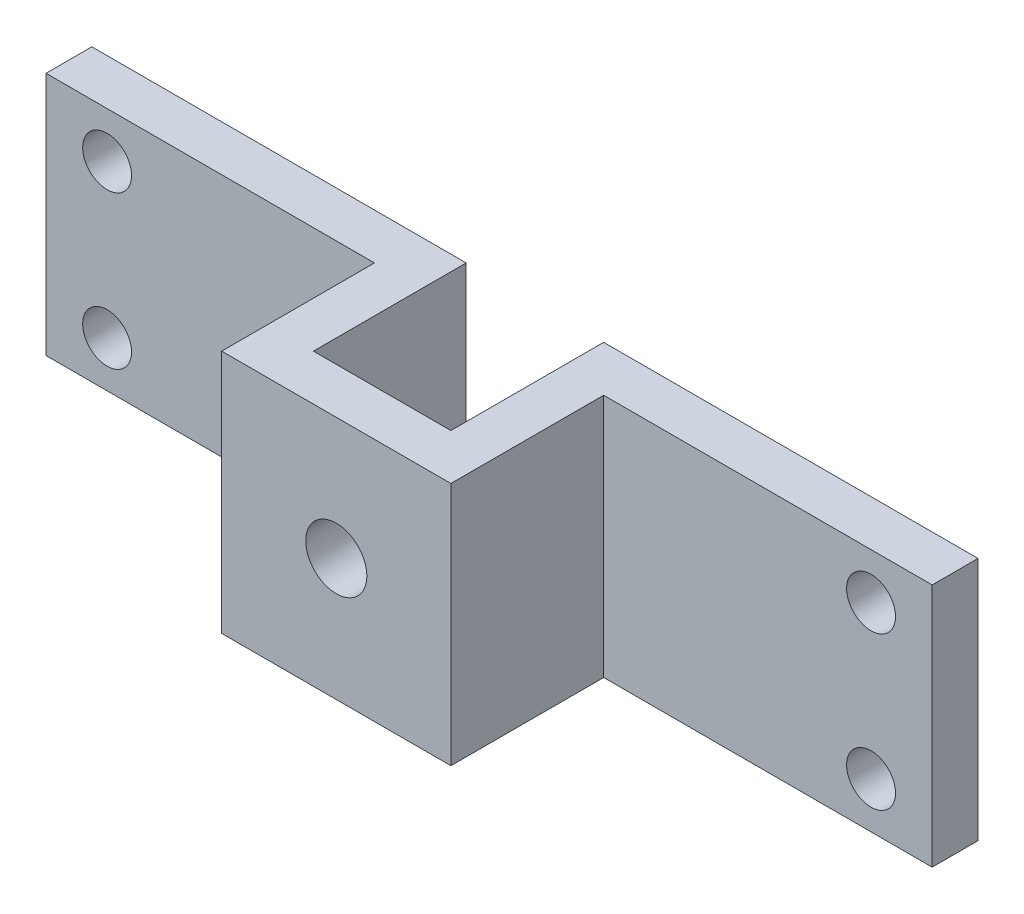
SolidWorks part; units mm, degrees
ref_plane "前视基准面" through (0, 0, 0) normal (0, 0, 1) x (1, 0, 0)
ref_plane "上视基准面" through (0, 0, 0) normal (0, 1, 0) x (1, 0, 0)
ref_plane "右视基准面" through (0, 0, 0) normal (1, 0, 0) x (0, 0, -1)
sketch "草图1" plane through (0, 0, 0) normal (0, 1, 0) x (1, 0, 0)
  line L0 (0, 0) -> (24.5, 0)
  line L1 (24.5, 0) -> (24.5, -10)
  line L2 (24.5, -10) -> (33.5, -10)
  line L3 (33.5, -10) -> (33.5, 0)
  line L4 (33.5, 0) -> (58, 0)
  line L5 (58, 0) -> (58, -3)
  line L6 (58, -3) -> (36.5, -3)
  line L7 (36.5, -3) -> (36.5, -13)
  line L8 (36.5, -13) -> (21.5, -13)
  line L9 (21.5, -13) -> (21.5, -3)
  line L10 (21.5, -3) -> (0, -3)
  line L11 (0, -3) -> (0, 0)
  line L12 (29, -13) -> (29, 15.7964) construction
  dimension "D1" = 3
  dimension "D2" = 24.5
  dimension "D3" = 3
  dimension "D4" = 24.5
  dimension "D5" = 58
  dimension "D6" = 10
  dimension "D7" = 10
  dimension "D8" = 3
  dimension "D9" = 9
extrude "凸台-拉伸1" add sketch "草图1" along normal blind 16
sketch "草图2" plane through (0, 0, 13) normal (0, 0, 1) x (1, 0, 0)
  line L1 (58, 16) -> (58, 0) construction
  line L2 (21.5, 16) -> (36.5, 16) construction
  line L5 (0, 16) -> (0, 0) construction
  line L6 (29, 0) -> (29, 16) construction
  line L7 (21.5, 0) -> (36.5, 0) construction
  line L8 (0, 8) -> (58, 8) construction
  circle A0 centre (29, 8) radius 2
  circle A5 centre (4, 13) radius 1.6
  circle A6 centre (4, 3) radius 1.6
  circle A7 centre (54, 13) radius 1.6
  circle A8 centre (54, 3) radius 1.6
  dimension "D1" = 4
  dimension "D2" = 4
  dimension "D3" = 10
  dimension "D4" = 3.1999
extrude "切除-拉伸1" cut sketch "草图2" against normal blind 16
